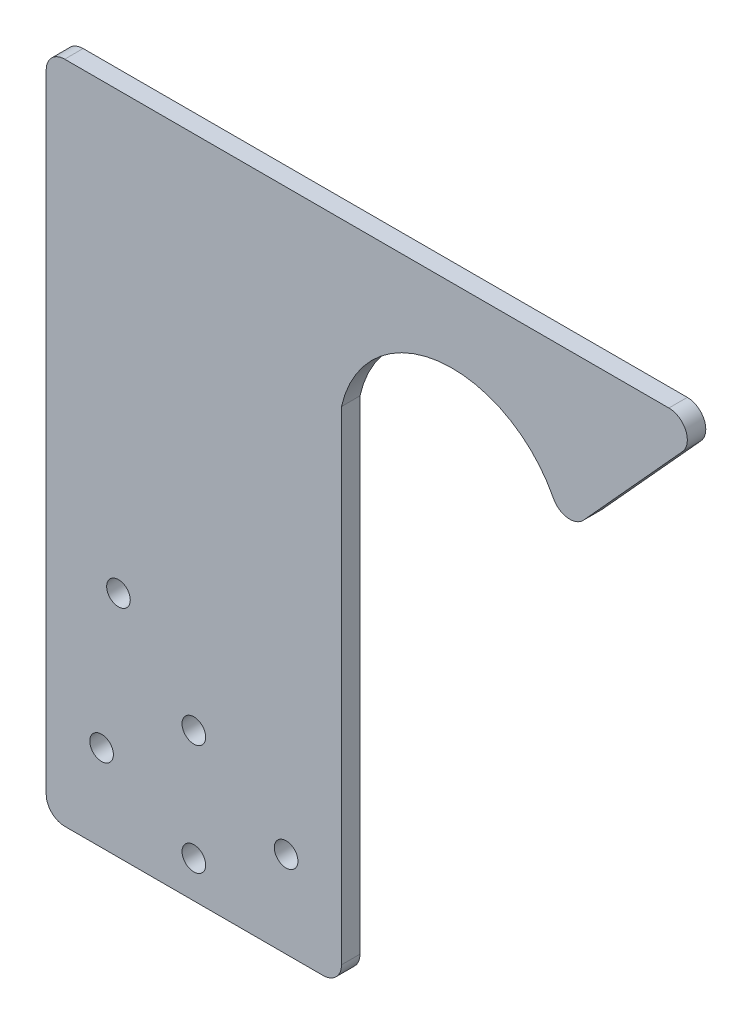
SolidWorks part; units mm, degrees
ref_plane "Front Plane" through (0, 0, 0) normal (0, 0, 1) x (1, 0, 0)
ref_plane "Top Plane" through (0, 0, 0) normal (0, 1, 0) x (1, 0, 0)
ref_plane "Right Plane" through (0, 0, 0) normal (1, 0, 0) x (0, 0, -1)
sketch "Sketch1" plane through (0, 0, 0) normal (0, 0, 1) x (1, 0, 0)
  line L1 (0, 114.3) -> (114.3, 114.3)
  line L2 (114.3, 114.3) -> (88.9, 86.354)
  line L3 (0, 0) -> (50.8, 0)
  line L4 (50.8, 0) -> (50.8, 86.354)
  line L5 (9.525, 14.8697) -> (41.275, 14.8697) construction
  line L6 (25.4, 14.8697) -> (25.4, 0) construction
  line L7 (0, 114.3) -> (0, 63.5)
  line L8 (0, 63.5) -> (0, 0)
  line L9 (50.8, 86.354) -> (88.9, 86.354) construction
  line L10 (69.85, 101.6) -> (69.85, 114.3) construction
  circle A0 centre (9.525, 14.8697) radius 2.032
  circle A1 centre (41.275, 14.8697) radius 2.032
  circle A2 centre (25.4, 6.35) radius 2.032
  circle A3 centre (25.4, 25.4) radius 2.032
  circle A4 centre (12.432, 39.3547) radius 2.032
  arc A5 (50.8, 86.354) -> (88.9, 86.354) centre (69.85, 82.0754) cw
  point P19 (88.9, 86.354)
  dimension "D3" = 63.5
  dimension "D5" = 4.064
  dimension "D6" = 31.75
  dimension "D11" = 50.8
  dimension "D2" = 114.3
  dimension "D4" = 50.8
  dimension "D7" = 19.05
  dimension "D8" = 6.35
  dimension "D9" = 19.05
  dimension "D10" = 19.05
  dimension "D12" = 38.1
  dimension "D13" = 12.7
extrude "Boss-Extrude1" add sketch "Sketch1" along normal blind 3.175
fillet "Fillet1" radius 3.175 5 edges at (0, 0, 1.5875) (50.8, 0, 1.5875) (88.9, 86.354, 1.5875) (114.3, 114.3, 1.5875) (0, 114.3, 1.5875)
